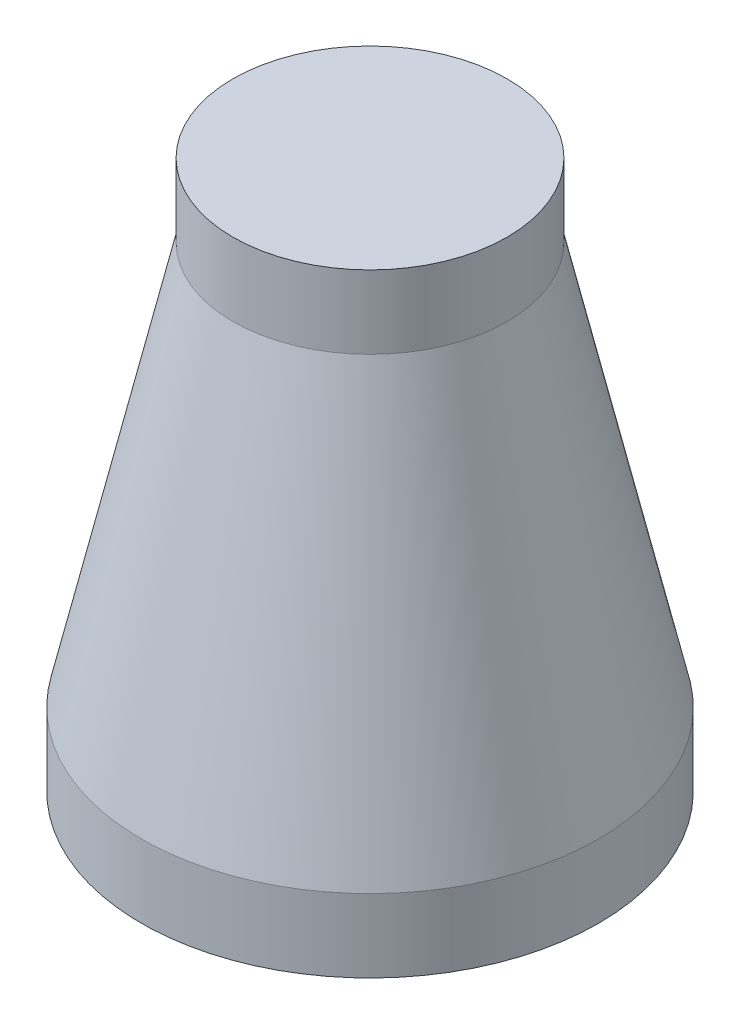
SolidWorks part; units mm, degrees
ref_plane "前视基准面" through (0, 0, 0) normal (0, 0, 1) x (1, 0, 0)
ref_plane "上视基准面" through (0, 0, 0) normal (0, 1, 0) x (1, 0, 0)
ref_plane "右视基准面" through (0, 0, 0) normal (1, 0, 0) x (0, 0, -1)
sketch "草图1" plane through (0, 0, 0) normal (0, 0, 1) x (1, 0, 0)
  line L0 (0, -8) -> (0, -52)
  line L1 (0, 0) -> (15, 0)
  line L2 (0, 0) -> (0, -8)
  line L4 (15, 0) -> (15, -8)
  line L6 (0, -52) -> (0, -60)
  line L7 (0, -60) -> (25, -60)
  line L8 (25, -52) -> (25, -60)
  line L9 (15, -8) -> (25, -52)
  dimension "D1" = 8
  dimension "D2" = 8
  dimension "D3" = 60
  dimension "D4" = 15
  dimension "D5" = 25
revolve "旋转1" add sketch "草图1" angle 360 about L0
